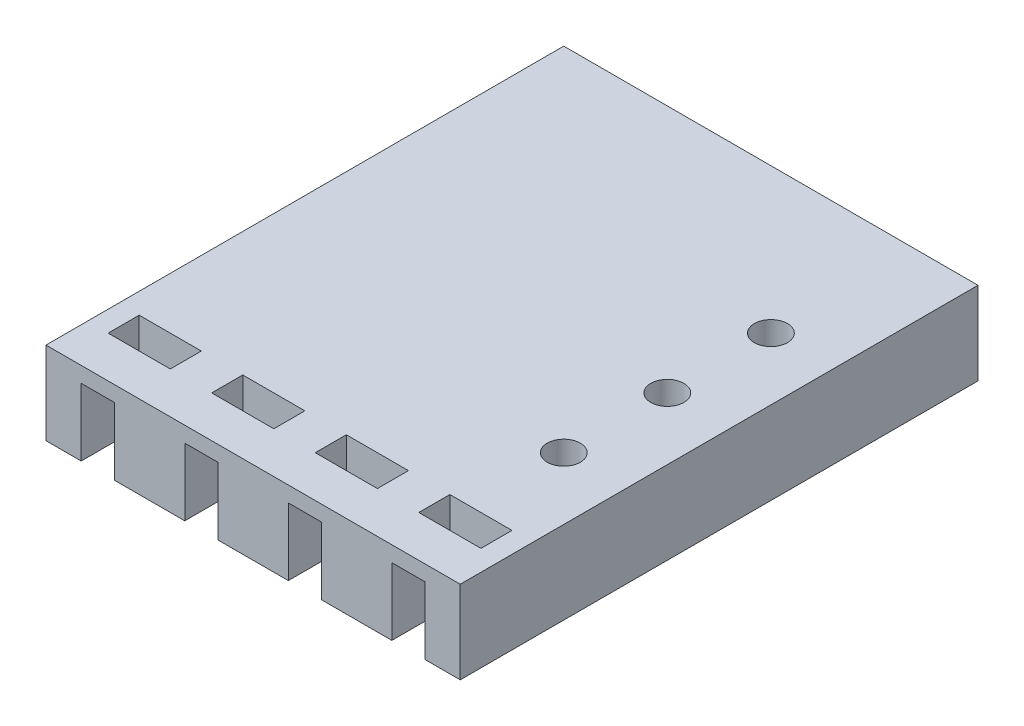
SolidWorks part; units mm, degrees
ref_plane "前视基准面" through (0, 0, 0) normal (0, 0, 1) x (1, 0, 0)
ref_plane "上视基准面" through (0, 0, 0) normal (0, 1, 0) x (1, 0, 0)
ref_plane "右视基准面" through (0, 0, 0) normal (1, 0, 0) x (0, 0, -1)
other "Configuration Table"
sketch "草图1" plane through (0, 0, 0) normal (0, 1, 0) x (1, 0, 0)
  line L1 (0, 0) -> (40, 0)
  line L2 (0, 0) -> (0, 50)
  line L3 (0, 50) -> (40, 50)
  line L4 (40, 0) -> (40, 50)
  dimension "D1" = 40
  dimension "D2" = 50
extrude "凸台-拉伸1" add sketch "草图1" along normal blind 8
sketch "草图2" plane through (0, 0, 0) normal (0, -1, 0) x (1, 0, 0)
  line L0 (0, 0) -> (40, 0) construction
  line L1 (3.4, 0) -> (6.6, 0)
  line L2 (3.4, 0) -> (3.4, -4)
  line L3 (3.4, -4) -> (6.6, -4)
  line L4 (6.6, 0) -> (6.6, -4)
  line L5 (0, -50) -> (0, 0) construction
  line L6 (16.6, 0) -> (16.6, -4)
  line L7 (13.4, -4) -> (16.6, -4)
  line L8 (13.4, 0) -> (13.4, -4)
  line L9 (13.4, 0) -> (16.6, 0)
  line L10 (26.6, 0) -> (26.6, -4)
  line L11 (23.4, -4) -> (26.6, -4)
  line L12 (23.4, 0) -> (23.4, -4)
  line L13 (23.4, 0) -> (26.6, 0)
  line L14 (36.6, 0) -> (36.6, -4)
  line L15 (33.4, -4) -> (36.6, -4)
  line L16 (33.4, 0) -> (33.4, -4)
  line L17 (33.4, 0) -> (36.6, 0)
  dimension "D1" = 4
  dimension "D2" = 3.2
  dimension "D3" = 3.4
  dimension "D4" = 4
extrude "切除-拉伸1" cut sketch "草图2" against normal blind 6.5
sketch "草图3" plane through (0, 0, 0) normal (0, -1, 0) x (1, 0, 0)
  line L1 (8, -4) -> (2, -4)
  line L2 (8, -4) -> (8, -7)
  line L3 (8, -7) -> (2, -7)
  line L4 (2, -4) -> (2, -7)
  line L5 (0, -50) -> (0, 0) construction
  line L6 (18, -7) -> (12, -7)
  line L7 (12, -4) -> (12, -7)
  line L8 (18, -4) -> (18, -7)
  line L9 (18, -4) -> (12, -4)
  line L10 (28, -7) -> (22, -7)
  line L11 (22, -4) -> (22, -7)
  line L12 (28, -4) -> (28, -7)
  line L13 (28, -4) -> (22, -4)
  line L14 (38, -7) -> (32, -7)
  line L15 (32, -4) -> (32, -7)
  line L16 (38, -4) -> (38, -7)
  line L17 (38, -4) -> (32, -4)
  dimension "D1" = 6
  dimension "D2" = 3
  dimension "D3" = 2
  dimension "D4" = 4
extrude "切除-拉伸2" cut sketch "草图3" against normal blind 16.5
sketch "草图10" plane through (0, 8, 0) normal (0, 1, 0) x (1, 0, 0)
  line L0 (25, 4) -> (25, 50004) construction
  line L1 (28, 4) -> (22, 4) construction
  line L2 (0, 0) -> (40, 0) construction
  circle A0 centre (34, 16) radius 1.6
  circle A1 centre (34, 26) radius 1.6
  circle A2 centre (34, 36) radius 1.6
  point P4 (25, 4)
  dimension "D1" = 9
  dimension "D2" = 16
  dimension "D3" = 3.2
  dimension "D4" = 3
extrude "切除-拉伸7" cut sketch "草图10" against normal blind 13
sketch "草图11" plane through (0, 0, 0) normal (0, -1, 0) x (1, 0, 0)
  line L0 (31, -23) -> (31, -29)
  line L1 (31, -33) -> (37, -33)
  line L2 (31, -33) -> (31, -39)
  line L3 (31, -39) -> (37, -39)
  line L4 (37, -33) -> (37, -39)
  line L5 (31, -33) -> (37, -39) construction
  line L6 (31, -39) -> (37, -33) construction
  line L7 (31, -23) -> (37, -23)
  line L8 (31, -29) -> (37, -29)
  line L9 (37, -23) -> (37, -29)
  line L10 (31, -13) -> (31, -19)
  line L11 (31, -13) -> (37, -13)
  line L12 (31, -19) -> (37, -19)
  line L13 (37, -13) -> (37, -19)
  point P0 (34, -36)
  dimension "D1" = 6
  dimension "D2" = 6
  dimension "D3" = 3
extrude "切除-拉伸8" cut sketch "草图11" against normal blind 3
